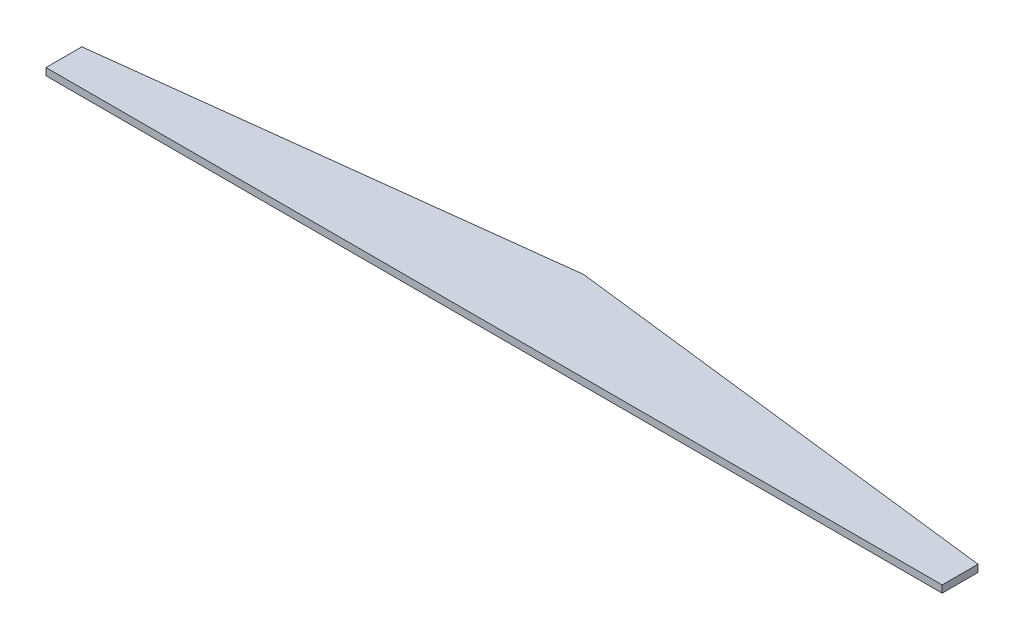
SolidWorks part; units mm, degrees
material "Balsa"
ref_plane "Front" through (0, 0, 0) normal (0, 0, 1) x (1, 0, 0)
ref_plane "Top" through (0, 0, 0) normal (0, 1, 0) x (1, 0, 0)
ref_plane "Right" through (0, 0, 0) normal (1, 0, 0) x (0, 0, -1)
sketch "Sketch1" plane through (0, 0, 0) normal (0, 1, 0) x (1, 0, 0)
  line L0 (0, 0) -> (500, 0)
  line L1 (500, 0) -> (500, 40)
  line L4 (0, 100) -> (500, 40)
  line L6 (-500, 40) -> (-500, 0)
  line L7 (-500, 0) -> (0, 0)
  line L8 (0, 100) -> (-500, 40)
  dimension "D1" = 500
  dimension "D2" = 500
  dimension "D3" = 100
  dimension "D4" = 40
  dimension "D5" = 40
extrude "Boss-Extrude1" add sketch "Sketch1" along normal blind 8
